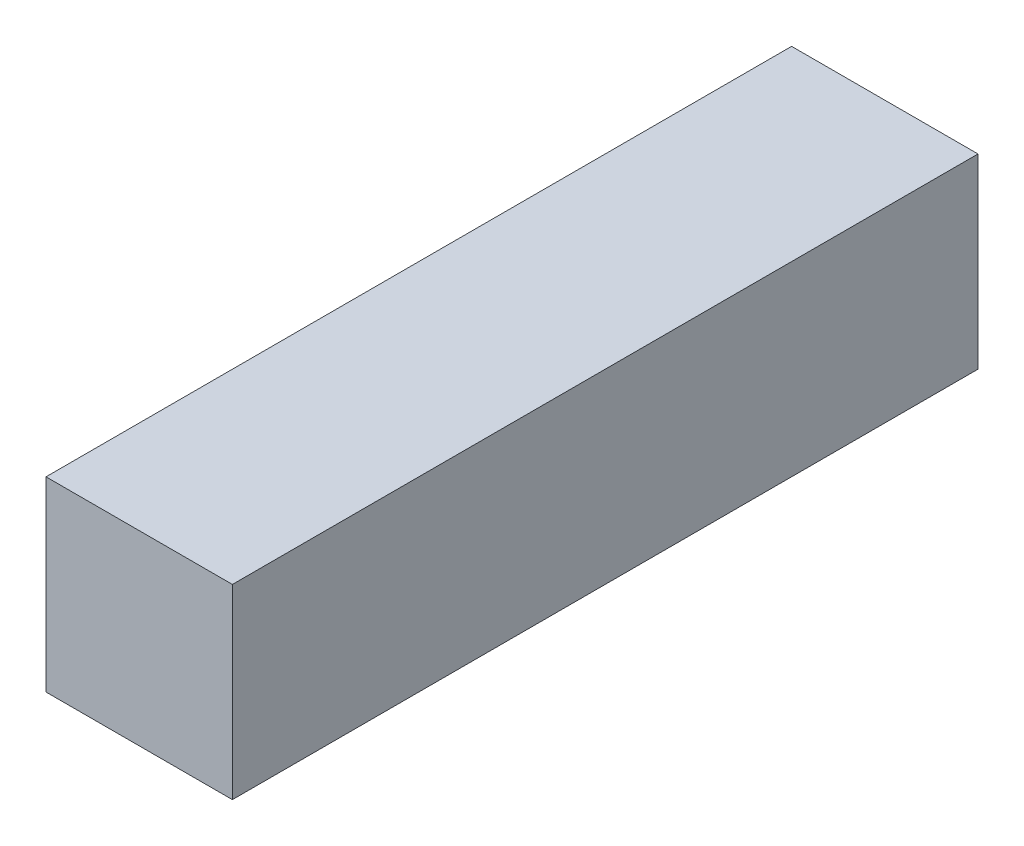
SolidWorks part; units mm, degrees
ref_plane "Front Plane" through (0, 0, 0) normal (0, 0, 1) x (1, 0, 0)
ref_plane "Top Plane" through (0, 0, 0) normal (0, 1, 0) x (1, 0, 0)
ref_plane "Right Plane" through (0, 0, 0) normal (1, 0, 0) x (0, 0, -1)
sketch "Sketch1" plane through (0, 0, 0) normal (0, 0, 1) x (1, 0, 0)
  line L8 (-4.75, 1.25) -> (-4.75, -1.75)
  line L9 (-4.75, 1.25) -> (-4.75, -1.75)
  line L10 (-4.75, -1.75) -> (-1.75, -1.75)
  line L11 (-4.75, -1.75) -> (-1.75, -1.75)
  line L12 (-1.75, -1.75) -> (-1.75, 1.25)
  line L13 (-1.75, -1.75) -> (-1.75, 1.25)
  line L14 (-1.75, 1.25) -> (-4.75, 1.25)
  line L15 (-1.75, 1.25) -> (-4.75, 1.25)
  dimension "D1" = 0
extrude "Boss-Extrude1" add sketch "Sketch1" along normal blind 12
